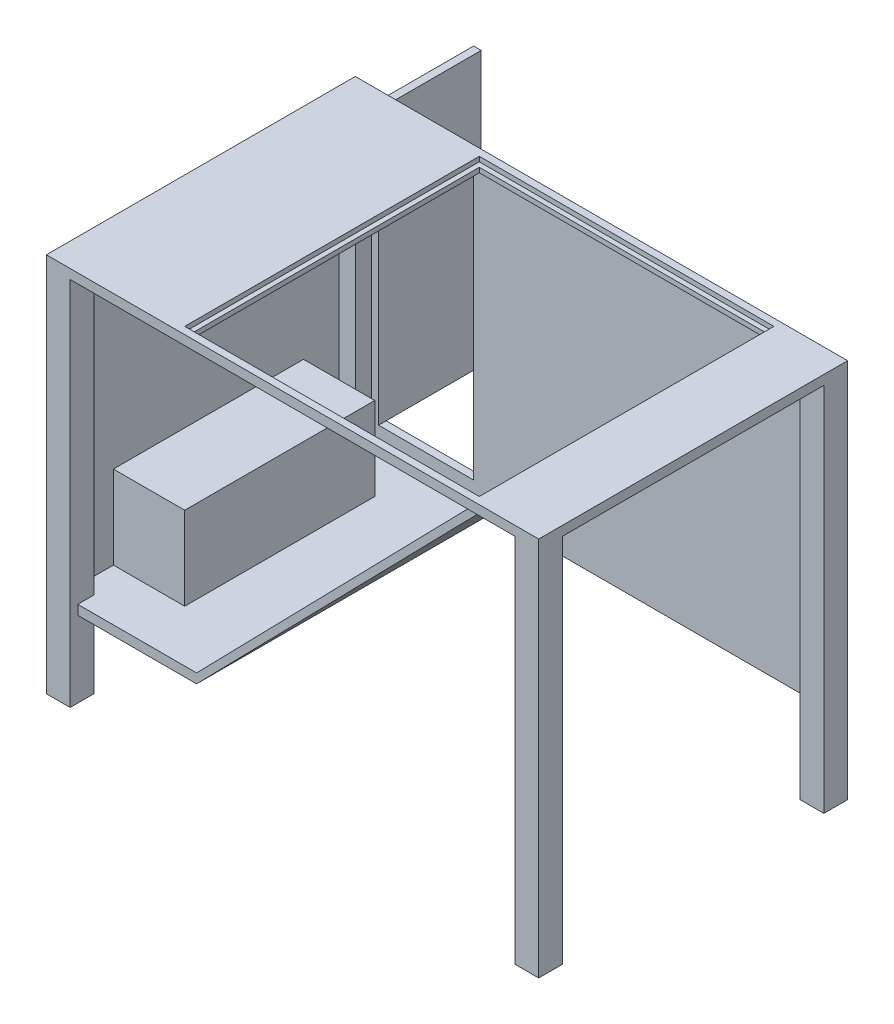
SolidWorks part; units mm, degrees
ref_plane "Plan de face" through (0, 0, 0) normal (0, 0, 1) x (1, 0, 0)
ref_plane "Plan de dessus" through (0, 0, 0) normal (0, 1, 0) x (1, 0, 0)
ref_plane "Plan de droite" through (0, 0, 0) normal (1, 0, 0) x (0, 0, -1)
sketch "Esquisse2" plane through (0, 0, 0) normal (0, 1, 0) x (1, 0, 0)
  line L1 (-41.7797, -601.4139) -> (994.2203, -601.4139)
  line L2 (-41.7797, -601.4139) -> (-41.7797, 48.5861)
  line L3 (-41.7797, 48.5861) -> (994.2203, 48.5861)
  line L4 (994.2203, -601.4139) -> (994.2203, 48.5861)
  dimension "D1" = 1036
  dimension "D2" = 650
extrude "Boss.-Extru.1" add sketch "Esquisse2" along normal blind 20
sketch "Esquisse3" plane through (0, 20, 0) normal (0, 1, 0) x (1, 0, 0)
  line L0 (-41.7797, 48.5861) -> (-41.7797, -601.4139) construction
  line L1 (234.2203, 33.5861) -> (854.2203, 33.5861)
  line L2 (234.2203, 33.5861) -> (234.2203, -586.4139)
  line L3 (234.2203, -586.4139) -> (854.2203, -586.4139)
  line L4 (854.2203, 33.5861) -> (854.2203, -586.4139)
  line L5 (994.2203, 48.5861) -> (-41.7797, 48.5861) construction
  dimension "D1" = 620
  dimension "D2" = 620
  dimension "D3" = 276
  dimension "D4" = 15
extrude "Enlèv. mat.-Extru.1" cut sketch "Esquisse3" against normal blind 10
sketch "Esquisse4" plane through (0, 10, 0) normal (0, 1, 0) x (1, 0, 0)
  line L0 (854.2203, 33.5861) -> (234.2203, 33.5861) construction
  line L1 (244.2203, 23.5861) -> (844.2203, 23.5861)
  line L2 (244.2203, 23.5861) -> (244.2203, -576.4139)
  line L3 (244.2203, -576.4139) -> (844.2203, -576.4139)
  line L4 (844.2203, 23.5861) -> (844.2203, -576.4139)
  line L5 (234.2203, 33.5861) -> (234.2203, -586.4139) construction
  dimension "D1" = 600
  dimension "D2" = 600
  dimension "D3" = 10
  dimension "D4" = 10
extrude "Enlèv. mat.-Extru.2" cut sketch "Esquisse4" against normal blind 10
sketch "Esquisse5" plane through (0, 0, 0) normal (0, -1, 0) x (1, 0, 0)
  line L1 (-41.7797, 601.4139) -> (8.2203, 601.4139)
  line L2 (-41.7797, 601.4139) -> (-41.7797, 551.4139)
  line L3 (-41.7797, 551.4139) -> (8.2203, 551.4139)
  line L4 (8.2203, 601.4139) -> (8.2203, 551.4139)
  line L6 (994.2203, 601.4139) -> (994.2203, 551.4139)
  line L9 (994.2203, 601.4139) -> (944.2203, 601.4139)
  line L14 (-41.7797, -48.5861) -> (8.2203, -48.5861)
  line L15 (-41.7797, -48.5861) -> (-41.7797, 1.4139)
  line L16 (-41.7797, 1.4139) -> (8.2203, 1.4139)
  line L17 (8.2203, -48.5861) -> (8.2203, 1.4139)
  line L18 (-41.7797, 601.4139) -> (994.2203, 601.4139) construction
  line L19 (944.2203, 601.4139) -> (944.2203, 551.4139)
  line L20 (944.2203, 551.4139) -> (994.2203, 551.4139)
  line L22 (994.2203, -48.5861) -> (944.2203, -48.5861)
  line L23 (994.2203, -48.5861) -> (994.2203, 1.4139)
  line L24 (994.2203, 1.4139) -> (944.2203, 1.4139)
  line L25 (944.2203, -48.5861) -> (944.2203, 1.4139)
  dimension "D1" = 50
  dimension "D2" = 50
  dimension "D3" = 50
  dimension "D4" = 50
  dimension "D5" = 50
  dimension "D6" = 50
  dimension "D7" = 50
  dimension "D8" = 50
extrude "Boss.-Extru.2" add sketch "Esquisse5" along normal blind 780
sketch "Esquisse6" plane through (0, 0, 0) normal (0, -1, 0) x (1, 0, 0)
  line L0 (8.2203, 1.4139) -> (-41.7797, 1.4139) construction
  line L1 (-41.7797, 551.4139) -> (-25.7797, 551.4139)
  line L2 (-41.7797, 551.4139) -> (-41.7797, 1.4139)
  line L3 (-41.7797, 1.4139) -> (-25.7797, 1.4139)
  line L4 (-25.7797, 551.4139) -> (-25.7797, 1.4139)
  dimension "D1" = 16
extrude "Boss.-Extru.3" add sketch "Esquisse6" along normal blind 620
sketch "Esquisse8" plane through (0, -620, 0) normal (0, -1, 0) x (1, 0, 0)
  line L0 (-25.7797, 551.4139) -> (8.2203, 551.4139)
  line L1 (8.2203, 551.4139) -> (8.2203, 585.4139)
  line L2 (8.2203, 551.4139) -> (8.2203, 601.4139) construction
  line L3 (8.2203, 601.4139) -> (944.2203, 601.4139) construction
  line L4 (8.2203, 585.4139) -> (258.2203, 585.4139)
  line L5 (-25.7797, 551.4139) -> (-25.7797, 1.4139)
  line L6 (-25.7797, 1.4139) -> (8.2203, 1.4139)
  line L7 (8.2203, 1.4139) -> (8.2203, -32.5861)
  line L8 (8.2203, -32.5861) -> (258.2203, -32.5861)
  line L9 (258.2203, -32.5861) -> (258.2203, 585.4139)
  dimension "D1" = 16
  dimension "D2" = 16
  dimension "D3" = 250
extrude "Boss.-Extru.5" add sketch "Esquisse8" against normal blind 20
sketch "Esquisse10" plane through (0, -600, 0) normal (0, 1, 0) x (1, 0, 0)
  line L0 (-25.7797, -551.4139) -> (-25.7797, -1.4139) construction
  line L1 (-25.7797, -76.4139) -> (124.2203, -76.4139)
  line L2 (-25.7797, -76.4139) -> (-25.7797, -476.4139)
  line L3 (-25.7797, -476.4139) -> (124.2203, -476.4139)
  line L4 (124.2203, -76.4139) -> (124.2203, -476.4139)
  line L5 (-25.7797, -1.4139) -> (8.2203, -1.4139) construction
  dimension "D1" = 150
  dimension "D2" = 400
  dimension "D3" = 75
extrude "Boss.-Extru.6" add sketch "Esquisse10" along normal blind 175
sketch "Esquisse20" plane through (-41.7797, 0, 0) normal (-1, 0, 0) x (0, 0, 1)
  line L0 (1.4139, -600) -> (1.4139, 0) construction
  line L1 (1.4139, 0) -> (551.4139, 0) construction
  circle A0 centre (31.4139, -30) radius 25
  dimension "D1" = 30
  dimension "D2" = 50
  dimension "D3" = 30
extrude "Enlèv. mat.-Extru.4" cut sketch "Esquisse20" against normal blind 16
sketch "Esquisse21" plane through (0, 0, -32.5861) normal (0, 0, -1) x (-1, 0, 0)
  line L1 (-944.2203, 0) -> (-8.2203, 0)
  line L2 (-944.2203, 0) -> (-944.2203, -620)
  line L3 (-944.2203, -620) -> (-8.2203, -620)
  line L4 (-8.2203, 0) -> (-8.2203, -620)
extrude "Boss.-Extru.7" add sketch "Esquisse21" along normal blind 16
sketch "Esquisse23" plane through (0, 0, 0) normal (0, -1, 0) x (1, 0, 0)
  line L0 (844.2203, -23.5861) -> (844.2203, -32.5861) construction
  line L1 (8.2203, -32.5861) -> (944.2203, -32.5861) construction
sketch "Esquisse24" plane through (0, 0, -32.5861) normal (0, 0, 1) x (1, 0, 0)
  line L0 (258.2203, -620) -> (258.2203, -600)
  line L1 (258.2203, -600) -> (844.2203, 0)
  line L2 (844.2203, 0) -> (864.2203, 0)
  line L3 (8.2203, 0) -> (944.2203, 0) construction
  line L4 (864.2203, 0) -> (258.2203, -620)
extrude "Boss.-Extru.8" add sketch "Esquisse24" along normal blind 618
sketch "Esquisse25" plane through (0, 0, -32.5861) normal (0, 0, 1) x (1, 0, 0)
  line L0 (8.2203, -600) -> (8.2203, 0) construction
  line L1 (23.2203, 0) -> (223.2203, 0)
  line L2 (23.2203, 0) -> (23.2203, -575)
  line L3 (23.2203, -575) -> (223.2203, -575)
  line L4 (223.2203, 0) -> (223.2203, -575)
  line L5 (8.2203, 0) -> (944.2203, 0) construction
  dimension "D1" = 15
  dimension "D2" = 200
  dimension "D3" = 575
  dimension "D4" = 0
extrude "Enlèv. mat.-Extru.5" cut sketch "Esquisse25" against normal blind 16
sketch "Esquisse26" plane through (0, 0, -48.5861) normal (0, 0, -1) x (-1, 0, 0)
  line L1 (-23.2203, 0) -> (-7.2203, 0)
  line L2 (-23.2203, 0) -> (-23.2203, -575)
  line L3 (-23.2203, -575) -> (-7.2203, -575)
  line L4 (-7.2203, 0) -> (-7.2203, -575)
  dimension "D1" = 16
extrude "Boss.-Extru.9" add sketch "Esquisse26" along normal blind 200
